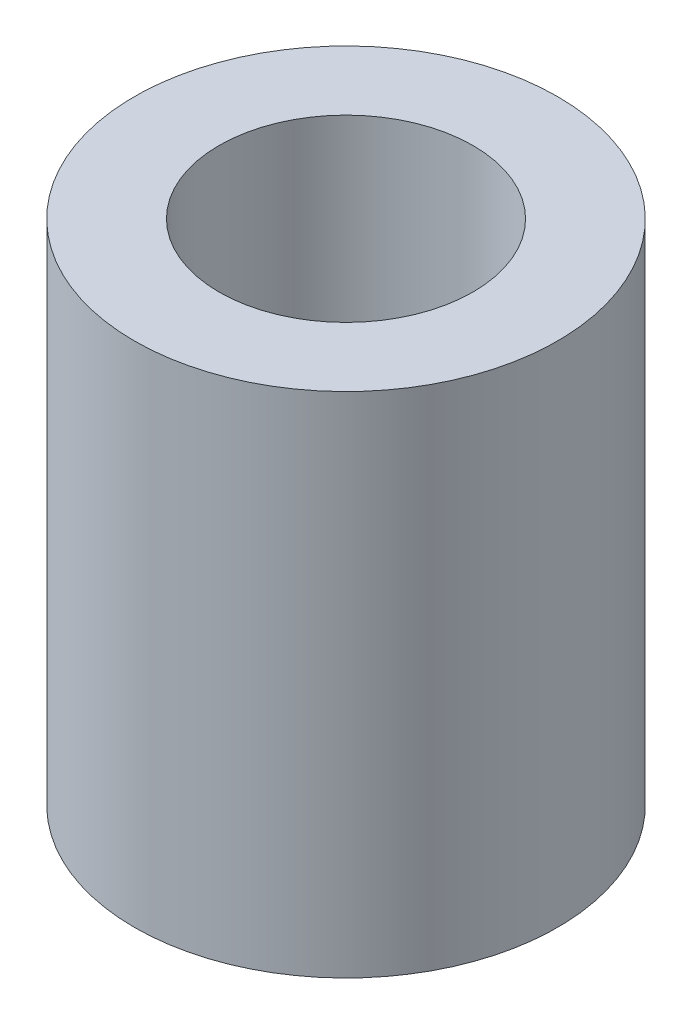
SolidWorks part; units mm, degrees
material "Galvanized Steel"
ref_plane "Front Plane" through (0, 0, 0) normal (0, 0, 1) x (1, 0, 0)
ref_plane "Top Plane" through (0, 0, 0) normal (0, 1, 0) x (1, 0, 0)
ref_plane "Right Plane" through (0, 0, 0) normal (1, 0, 0) x (0, 0, -1)
sketch "Sketch1" plane through (0, 0, 0) normal (0, 1, 0) x (1, 0, 0)
  circle A0 centre (0, 0) radius 15.875
  circle A1 centre (0, 0) radius 9.525
  dimension "D1" = 31.75
  dimension "D2" = 19.05
extrude "Boss-Extrude1" add sketch "Sketch1" along normal blind 38.1
